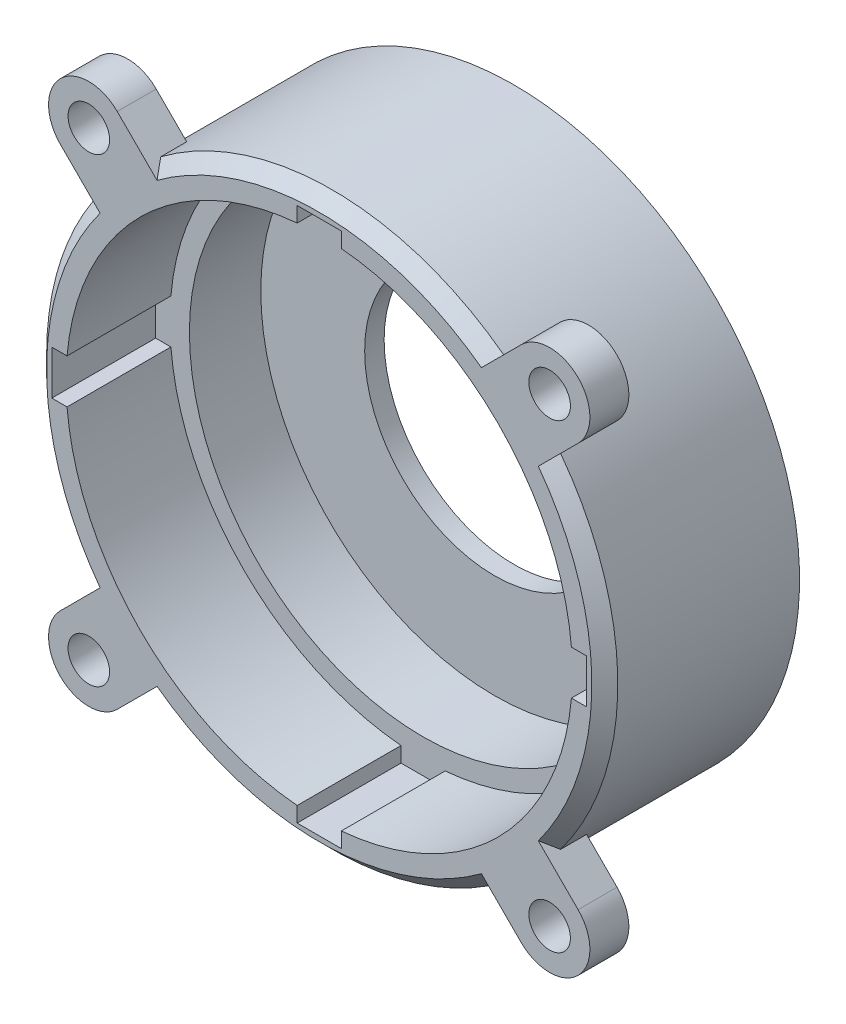
SolidWorks part; units mm, degrees
ref_plane "Front Plane" through (0, 0, 0) normal (0, 0, 1) x (1, 0, 0)
ref_plane "Top Plane" through (0, 0, 0) normal (0, 1, 0) x (1, 0, 0)
ref_plane "Right Plane" through (0, 0, 0) normal (1, 0, 0) x (0, 0, -1)
sketch "Sketch1" plane through (0, 0, 0) normal (0, 0, 1) x (1, 0, 0)
  circle A0 centre (0, 0) radius 22
  dimension "D1" = 44
extrude "Boss-Extrude1" add sketch "Sketch1" along normal mid plane 16.5
sketch "Sketch2" plane through (0, 0, 8.25) normal (0, 0, 1) x (1, 0, 0)
  circle A0 centre (0, 0) radius 18
  dimension "D1" = 36
extrude "Cut-Extrude1" cut sketch "Sketch2" against normal blind 13.5
sketch "Sketch3" plane through (0, 0, 8.25) normal (0, 0, 1) x (1, 0, 0)
  circle A0 centre (0, 0) radius 19.5
  dimension "D1" = 39
extrude "Cut-Extrude2" cut sketch "Sketch3" against normal blind 8
sketch "Sketch4" plane through (0, 0, -8.25) normal (0, 0, -1) x (-1, 0, 0)
  circle A0 centre (0, 0) radius 10
  dimension "D1" = 20
extrude "Cut-Extrude3" cut sketch "Sketch4" against normal through all both and the other way through all
sketch "Sketch6" plane through (0, 0, 8.25) normal (0, 0, 1) x (1, 0, 0)
  line L1 (1.7, 20.6) -> (-1.7, 20.6)
  line L2 (1.7, 20.6) -> (1.7, 18.4)
  line L3 (1.7, 18.4) -> (-1.7, 18.4)
  line L4 (-1.7, 20.6) -> (-1.7, 18.4)
  line L5 (1.7, 20.6) -> (-1.7, 18.4) construction
  line L6 (1.7, 18.4) -> (-1.7, 20.6) construction
  circle A0 centre (0, 0) radius 19.5 construction
  circle A1 centre (0, 0) radius 19.5 construction
  point P0 (0, 19.5)
  dimension "D1" = 2.2
  dimension "D2" = 3.4
extrude "Cut-Extrude5" cut sketch "Sketch6" against normal up to surface (8 mm away) up to face at (19.5, 0, 0.25)
pattern_circular "CirPattern1" count 4 over 360 about axis through (0, 0, 0) along (0, 0, 1) of "Cut-Extrude5"
sketch "Sketch7" plane through (0, 0, -8.25) normal (0, 0, -1) x (-1, 0, 0)
  circle A0 centre (0, 0) radius 22
extrude "Cut-Extrude6" cut sketch "Sketch7" against normal blind 1.5
chamfer "Chamfer1" distance 1 angle 45 1 edges at (22, 0, 8.25)
sketch "Sketch8" plane through (0, 0, 8.25) normal (0, 0, 1) x (1, 0, 0)
  line L1 (15.5563, 19.9404) -> (12.4945, 16.8786)
  line L6 (19.9404, 15.5563) -> (16.8786, 12.4945)
  line L7 (12.4945, 16.8786) -> (16.8786, 12.4945)
  circle A2 centre (17.7484, 17.7484) radius 1.6
  arc A4 (19.9404, 15.5563) -> (15.5563, 19.9404) centre (17.7484, 17.7484) ccw
  circle A6 centre (0, 0) radius 21 construction
  point P2 (0, 0)
  point P9 (0, 0)
extrude "Boss-Extrude2" add sketch "Sketch8" against normal blind 3
pattern_circular "CirPattern2" count 4 over 360 about axis through (0, 0, 0) along (0, 0, 1) of "Boss-Extrude2"
